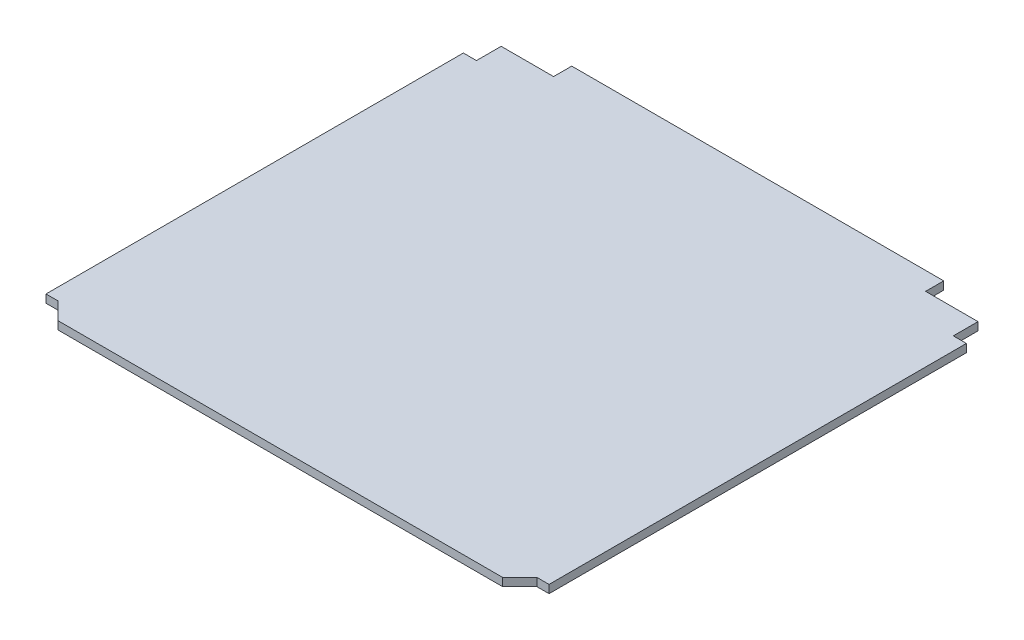
SolidWorks part; units mm, degrees
ref_plane "Front Plane" through (0, 0, 0) normal (0, 0, 1) x (1, 0, 0)
ref_plane "Top Plane" through (0, 0, 0) normal (0, 1, 0) x (1, 0, 0)
ref_plane "Right Plane" through (0, 0, 0) normal (1, 0, 0) x (0, 0, -1)
sketch "Sketch2" plane through (0, 0, 0) normal (0, 1, 0) x (1, 0, 0)
  line L0 (41.5, -47.4) -> (47.4, -41.5)
  line L1 (47.4, -41.5) -> (50, -41.5)
  line L2 (50, -41.5) -> (50, 41.5)
  line L3 (50, 41.5) -> (47.4, 41.5)
  line L4 (47.4, 41.5) -> (47.4, 46.4)
  line L8 (37, 46.4) -> (37, 50)
  line L9 (37, 50) -> (-37, 50)
  line L10 (-37, 50) -> (-37, 46.4)
  line L14 (-47.4, 46.4) -> (-47.4, 41.5)
  line L15 (-47.4, 41.5) -> (-50, 41.5)
  line L16 (-50, 41.5) -> (-50, -41.5)
  line L17 (-50, -41.5) -> (-47.4, -41.5)
  line L18 (-47.4, -41.5) -> (-41.5, -47.4)
  line L19 (-41.5, -47.4) -> (41.5, -47.4)
  line L20 (47.4, 46.4) -> (37, 46.4)
  line L21 (-47.4, 46.4) -> (-37, 46.4)
extrude "Boss-Extrude1" add sketch "Sketch2" along normal mid plane 1.6
sketch "Sketch3" plane through (0, 0, 0) normal (0, 1, 0) x (1, 0, 0)
  line L24 (-47.4, -41.5) -> (-47.5, -41.4)
  line L25 (47.4, -41.5) -> (47.5, -41.4)
  line L49 (-36.9, 46.3) -> (-47.3, 46.3)
  line L50 (-47.3, 46.3) -> (-47.3, 41.4)
  line L51 (-47.3, 41.4) -> (-49.9, 41.4)
  line L52 (-49.9, 41.4) -> (-49.9, -41.4)
  line L53 (-49.9, -41.4) -> (-47.3586, -41.4)
  line L54 (-47.3586, -41.4) -> (-41.4586, -47.3)
  line L55 (-41.4586, -47.3) -> (41.4586, -47.3)
  line L56 (41.4586, -47.3) -> (47.3586, -41.4)
  line L57 (47.3586, -41.4) -> (49.9, -41.4)
  line L58 (49.9, -41.4) -> (49.9, 41.4)
  line L59 (49.9, 41.4) -> (47.3, 41.4)
  line L61 (47.3, 41.4) -> (47.3, 46.3)
  line L62 (47.3, 46.3) -> (36.9, 46.3)
  line L63 (36.9, 46.3) -> (36.9, 49.9)
  line L64 (36.9, 49.9) -> (-36.9, 49.9)
  line L65 (-36.9, 49.9) -> (-36.9, 46.3)
  line L66 (-36.9, 46.3) -> (-47.3, 46.3)
  line L67 (-47.3, 46.3) -> (-47.3, 41.4)
  line L68 (-47.3, 41.4) -> (-49.9, 41.4)
  line L69 (-49.9, 41.4) -> (-49.9, -41.4)
  line L70 (-49.9, -41.4) -> (-47.5, -41.4)
  line L74 (47.5, -41.4) -> (49.9, -41.4)
  line L75 (49.9, -41.4) -> (49.9, 41.4)
  line L76 (49.9, 41.4) -> (47.3, 41.4)
  line L77 (47.3, 41.4) -> (47.3, 46.3)
  line L78 (47.3, 46.3) -> (36.9, 46.3)
  line L79 (36.9, 46.3) -> (36.9, 49.9)
  line L80 (36.9, 49.9) -> (-36.9, 49.9)
  line L81 (-36.9, 49.9) -> (-36.9, 46.3)
  line L89 (-37, 46.4) -> (-47.4, 46.4)
  line L90 (-47.4, 46.4) -> (-47.4, 41.5)
  line L91 (-47.4, 41.5) -> (-50, 41.5)
  line L92 (-50, 41.5) -> (-50, -41.5)
  line L93 (-50, -41.5) -> (-47.4, -41.5)
  line L94 (-47.4, -41.5) -> (-41.5, -47.4)
  line L95 (-41.5, -47.4) -> (41.5, -47.4)
  line L96 (41.5, -47.4) -> (47.4, -41.5)
  line L97 (47.4, -41.5) -> (50, -41.5)
  line L98 (50, -41.5) -> (50, 41.5)
  line L99 (50, 41.5) -> (47.4, 41.5)
  line L100 (47.4, 41.5) -> (47.4, 46.4)
  line L101 (47.4, 46.4) -> (37, 46.4)
  line L102 (37, 46.4) -> (37, 50)
  line L103 (37, 50) -> (-37, 50)
  line L104 (-37, 50) -> (-37, 46.4)
  line L105 (-37, 46.4) -> (-47.4, 46.4)
  line L106 (-47.4, 46.4) -> (-47.4, 41.5)
  line L107 (-47.4, 41.5) -> (-50, 41.5)
  line L108 (-50, 41.5) -> (-50, -41.5)
  line L109 (-50, -41.5) -> (-47.4, -41.5)
  line L110 (-47.4, -41.5) -> (-41.5, -47.4)
  line L111 (-41.5, -47.4) -> (41.5, -47.4)
  line L112 (41.5, -47.4) -> (47.4, -41.5)
  line L113 (47.4, -41.5) -> (50, -41.5)
  line L114 (50, -41.5) -> (50, 41.5)
  line L115 (50, 41.5) -> (47.4, 41.5)
  line L116 (47.4, 41.5) -> (47.4, 46.4)
  line L117 (47.4, 46.4) -> (37, 46.4)
  line L118 (37, 46.4) -> (37, 50)
  line L119 (37, 50) -> (-37, 50)
  line L120 (-37, 50) -> (-37, 46.4)
  dimension "D2" = 0
  dimension "D1" = 0.1
extrude "AddTolerance" cut sketch "Sketch3" against normal through all both and the other way through all contours L119 L120 L105 L106 L107 L108 L109 L24 L70 L69 L68 L67 L66 L81 L80 L79 L78 L77 L76 L75 L74 L25 L113 L114 L115 L116 L117 L118
sketch "Sketch4" plane through (0, 0, 0) normal (0, 1, 0) x (1, 0, 0)
  line L0 (41.5, -47.4) -> (47.5, -41.4) construction
  line L1 (-41.5, -47.4) -> (41.5, -47.4) construction
  line L2 (-47.5, -41.4) -> (-41.5, -47.4) construction
  line L3 (41.5, -47.4) -> (47.5, -41.4)
  line L4 (-41.5, -47.4) -> (41.5, -47.4)
  line L5 (-47.5, -41.4) -> (-41.5, -47.4)
  line L6 (43.1, -45.8) -> (-43.1, -45.8)
  line L9 (-44.1, -44.8) -> (44.1, -44.8)
  dimension "D1" = 1.6
  dimension "D2" = 1
extrude "Cut-Extrude1" cut sketch "Sketch4" against normal through all both and the other way through all contours L3 L6 L5 L4 | L9 L5 L6 L3
